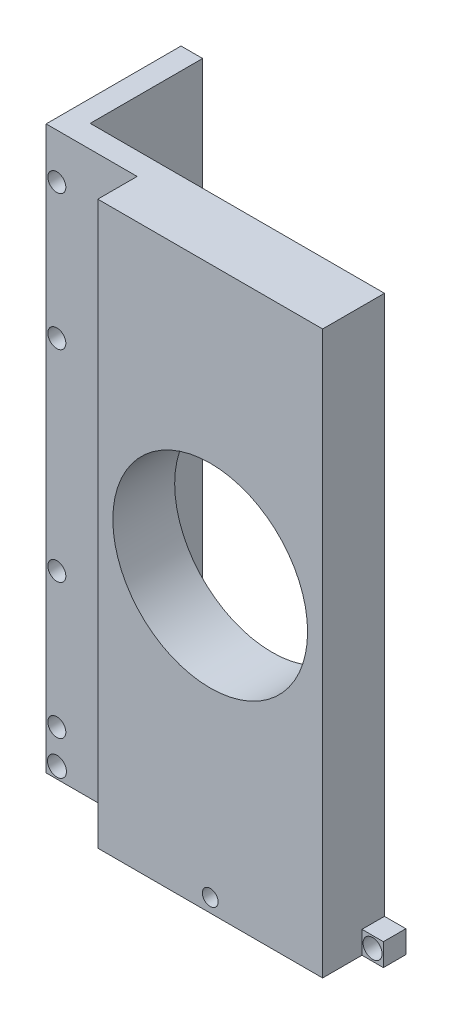
SolidWorks part; units mm, degrees
ref_plane "Front Plane" through (0, 0, 0) normal (0, 0, 1) x (1, 0, 0)
ref_plane "Top Plane" through (0, 0, 0) normal (0, 1, 0) x (1, 0, 0)
ref_plane "Right Plane" through (0, 0, 0) normal (1, 0, 0) x (0, 0, -1)
sketch "Sketch1" plane through (0, 0, 0) normal (0, 0, 1) x (1, 0, 0)
  line L0 (19.05, 31.75) -> (16.632, 31.75)
  line L1 (-19.05, 31.75) -> (19.05, 31.75)
  line L2 (-19.05, 31.75) -> (-19.05, -31.75)
  line L3 (-19.05, -31.75) -> (19.05, -31.75)
  line L4 (19.05, 31.75) -> (19.05, -31.75)
  line L5 (-19.05, 31.75) -> (19.05, -31.75) construction
  line L6 (-19.05, -31.75) -> (19.05, 31.75) construction
  line L7 (19.05, 31.75) -> (16.632, 31.75)
  line L8 (19.05, 31.75) -> (19.05, -31.75)
  line L9 (19.05, -31.75) -> (16.632, -31.75)
  line L10 (16.632, 31.75) -> (16.632, -31.75)
  line L11 (-19.05, 31.75) -> (-16.6124, 31.75)
  line L12 (-19.05, 31.75) -> (-19.05, -31.75)
  line L13 (-19.05, -31.75) -> (-16.6124, -31.75)
  line L14 (-16.6124, 31.75) -> (-16.6124, -31.75)
  line L15 (17.841, 31.75) -> (17.841, 26.6578)
  line L16 (17.841, 26.6578) -> (17.841, 11.3858)
  line L17 (19.05, 0) -> (17.841, 0)
  line L18 (0, 31.75) -> (0, 21.4812) construction
  circle A0 centre (17.841, 26.6578) radius 1.016
  circle A1 centre (17.841, 11.3858) radius 1.016
  circle A2 centre (17.841, -26.6578) radius 1.016
  circle A3 centre (17.841, -11.3858) radius 1.016
  circle A4 centre (-17.841, -26.6578) radius 1.016
  circle A5 centre (-17.841, -11.3858) radius 1.016
  circle A6 centre (-17.841, 11.3858) radius 1.016
  circle A7 centre (-17.841, 26.6578) radius 1.016
  point P0 (0, 0)
  point P31 (0, 0)
  dimension "D1" = 63.5
  dimension "D2" = 38.1
extrude "Boss-Extrude1" add sketch "Sketch1" against normal blind 15.24
sketch "Sketch2" plane through (0, 0, 0) normal (0, 0, 1) x (1, 0, 0)
  line L0 (-16.6124, 31.75) -> (-16.6124, -31.75) construction
  line L1 (16.632, 31.75) -> (-16.6124, 31.75)
  line L2 (16.632, 31.75) -> (16.632, -31.75)
  line L3 (16.632, -31.75) -> (-16.6124, -31.75)
  line L4 (-16.6124, 31.75) -> (-16.6124, -31.75)
extrude "Boss-Extrude2" add sketch "Sketch2" against normal blind 2.54
sketch "Sketch3" plane through (0, -31.75, 0) normal (0, -1, 0) x (1, 0, 0)
  line L1 (-19.05, 0) -> (19.05, 0)
  line L2 (-19.05, 0) -> (-19.05, -12.7)
  line L3 (-19.05, -12.7) -> (19.05, -12.7)
  line L4 (19.05, 0) -> (19.05, -12.7)
extrude "Boss-Extrude3" add sketch "Sketch3" against normal blind 2.54
sketch "Sketch4" plane through (0, 0, 0) normal (0, 0, 1) x (1, 0, 0)
  circle A0 centre (-17.841, -26.6578) radius 1.016
sketch "Sketch5" plane through (0, 0, 0) normal (0, 0, 1) x (1, 0, 0)
  line L0 (-19.05, -30.48) -> (-17.8278, -30.48) construction
  line L1 (-19.05, -29.21) -> (-19.05, -31.75) construction
  line L2 (0, -31.8452) -> (0, -30.6248) construction
  circle A0 centre (-17.8278, -30.48) radius 1.0717
  circle A1 centre (17.8278, -30.48) radius 1.0717
extrude "Cut-Extrude2" cut sketch "Sketch5" against normal through all contours A1 | A0
sketch "Sketch6" plane through (0, 0, 0) normal (0, 0, 1) x (1, 0, 0)
  circle A0 centre (17.841, -26.6578) radius 1.016
extrude "Cut-Extrude3" cut sketch "Sketch6" against normal through all
sketch "Sketch7" plane through (0, 0, -12.7) normal (0, 0, -1) x (-1, 0, 0)
  line L1 (-19.05, -29.21) -> (19.05, -29.21)
  line L2 (-19.05, -29.21) -> (-19.05, -31.75)
  line L3 (-19.05, -31.75) -> (19.05, -31.75)
  line L4 (19.05, -29.21) -> (19.05, -31.75)
  circle A0 centre (-17.8278, -30.48) radius 1.0717
extrude "Boss-Extrude5" add sketch "Sketch7" along normal blind 2.54
sketch "Sketch8" plane through (0, 0, 0) normal (0, 0, 1) x (1, 0, 0)
  line L0 (16.632, 1.27) -> (-8.768, 1.27)
  line L1 (16.632, -29.21) -> (16.632, 31.75) construction
  circle A0 centre (3.932, 1.27) radius 11
  dimension "D1" = 25.4
extrude "Cut-Extrude4" cut sketch "Sketch8" against normal through all contours L0 A0 | L0 A0
sketch "Sketch9" plane through (0, 0, 0) normal (0, 0, 1) x (1, 0, 0)
  line L0 (-19.05, -31.75) -> (19.05, -31.75) construction
  line L1 (16.632, 31.75) -> (-8.768, 31.75)
  line L2 (16.632, 31.75) -> (16.632, -31.75)
  line L3 (16.632, -31.75) -> (-8.768, -31.75)
  line L4 (-8.768, 31.75) -> (-8.768, -31.75)
  circle A0 centre (3.932, 1.27) radius 11
  dimension "D1" = 25.4
extrude "Boss-Extrude6" add sketch "Sketch9" along normal blind 4.445
sketch "Sketch10" plane through (0, 0, -15.24) normal (0, 0, -1) x (-1, 0, 0)
  line L0 (19.05, -31.75) -> (-19.05, -31.75) construction
  line L1 (-19.05, -29.21) -> (16.6124, -29.21)
  line L2 (-19.05, -29.21) -> (-19.05, -31.75)
  line L3 (-19.05, -31.75) -> (16.6124, -31.75)
  line L4 (16.6124, -29.21) -> (16.6124, -31.75)
extrude "Cut-Extrude5" cut sketch "Sketch10" against normal blind 12.7
sketch "Sketch11" plane through (0, 0, 4.445) normal (0, 0, 1) x (1, 0, 0)
  circle A0 centre (3.932, -30.2179) radius 0.889
extrude "Cut-Extrude7" cut sketch "Sketch11" against normal blind 12.7
